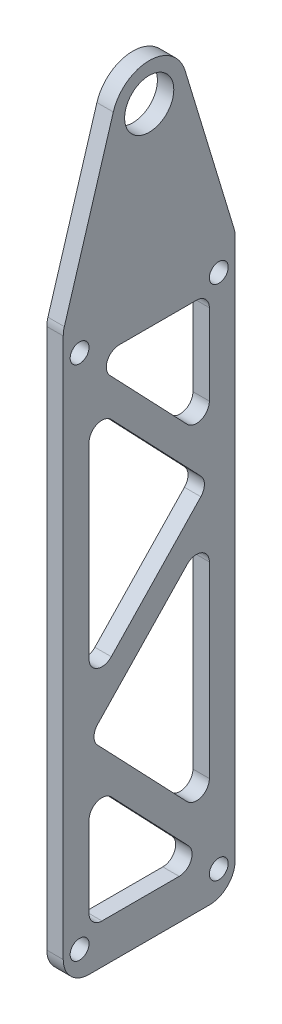
SolidWorks part; units mm, degrees
material "6061 Alloy"
ref_plane "Front Plane" through (0, 0, 0) normal (0, 0, 1) x (1, 0, 0)
ref_plane "Top Plane" through (0, 0, 0) normal (0, 1, 0) x (1, 0, 0)
ref_plane "Right Plane" through (0, 0, 0) normal (1, 0, 0) x (0, 0, -1)
sketch "Sketch1" plane through (0, 0, 0) normal (1, 0, 0) x (0, 0, -1)
  line L0 (-13.4747, 0) -> (13.4747, 0) construction
  line L1 (0, 0) -> (0, 35) construction
  line L2 (-13.4747, 0) -> (0, 35) construction
  line L3 (0, 35) -> (13.4747, 0) construction
  line L4 (13.4747, 0) -> (-13.4747, 0) construction
  line L8 (-13.4747, 0) -> (13.4747, 0) construction
  line L9 (-13.4747, 0) -> (-13.4747, -100) construction
  line L10 (13.4747, 0) -> (13.4747, -100) construction
  line L11 (-13.4747, -100) -> (13.4747, -100) construction
  line L16 (-16.645, -105.15) -> (16.645, -105.15)
  line L17 (-16.645, -105.15) -> (-16.645, 5.15)
  line L18 (16.645, -105.15) -> (16.645, 5.15)
  line L19 (-16.645, 5.15) -> (16.645, 5.15)
  line L20 (-16.645, 5.15) -> (-6.9497, 37.1084)
  line L21 (-6.9497, 37.1084) -> (6.9497, 37.1084) construction
  line L22 (6.9497, 37.1084) -> (16.645, 5.15)
  circle A0 centre (-13.4747, 0) radius 1.8288
  circle A1 centre (0, 35) radius 4.7625
  circle A2 centre (13.4747, 0) radius 1.8288
  circle A3 centre (-13.4747, -100) radius 1.8288
  circle A4 centre (13.4747, -100) radius 1.8288
  arc A5 (-6.9497, 37.1084) -> (6.9497, 37.1084) centre (0, 35) cw
  point P4 (0, 0)
  point P7 (0, -105.15)
  dimension "D3" = 3.6576
  dimension "D4" = 9.525
  dimension "D9" = 2.5
  dimension "D1" = 26.9494
  dimension "D5" = 100
  dimension "D6" = 5.15
  dimension "D7" = 35
  dimension "D8" = 5.15
  dimension "D2" = 33.29
extrude "Boss-Extrude1" add sketch "Sketch1" along normal blind 3.175
sketch "Sketch2" plane through (3.175, 0, 0) normal (1, 0, 0) x (0, 0, -1)
  line L3 (-11.645, -97.42) -> (-11.645, -2.5) construction
  line L4 (11.645, -97.42) -> (11.645, -2.5) construction
  line L5 (-11.645, -2.5) -> (11.645, -2.5) construction
  line L6 (-11.645, -97.42) -> (11.645, -97.42) construction
  line L8 (-16.645, -105.15) -> (-16.645, 5.15) construction
  line L9 (11.645, -2.5) -> (-11.645, -2.5)
  line L10 (-11.645, -2.5) -> (11.645, -26.8987)
  line L11 (11.645, -26.8987) -> (11.645, -2.5)
  line L12 (-11.645, -9.7413) -> (11.645, -34.14)
  line L13 (11.645, -34.14) -> (-11.645, -58.5387)
  line L14 (-11.645, -58.5387) -> (-11.645, -34.14)
  line L15 (11.645, -37.7607) -> (-11.645, -62.1593) construction
  line L16 (-11.645, -34.14) -> (-11.645, -9.7413)
  line L17 (-11.645, -73.0213) -> (-11.645, -97.42)
  line L18 (-11.645, -97.42) -> (11.645, -97.42)
  line L19 (11.645, -97.42) -> (-11.645, -73.0213)
  line L20 (11.645, -41.3813) -> (11.645, -65.78)
  line L21 (11.645, -65.78) -> (11.645, -90.1787)
  line L22 (11.645, -90.1787) -> (-11.645, -65.78)
  line L23 (-11.645, -65.78) -> (11.645, -41.3813)
  line L24 (16.645, -105.15) -> (16.645, 5.15) construction
  circle A1 centre (13.4747, 0) radius 1.8288 construction
  circle A3 centre (13.4747, -100) radius 1.8288 construction
  point P0 (11.645, -49.96)
  point P2 (0, -97.42)
  point P28 (0, -49.96)
  dimension "D4" = 2.58
  dimension "D1" = 5
  dimension "D2" = 5
  dimension "D3" = 2.5
  dimension "D5" = 5
  dimension "D6" = 2.5
  dimension "D7" = 2
extrude "Cut-Extrude1" cut sketch "Sketch2" against normal through all
fillet "Fillet1" radius 2.5 12 edges at (1.5875, -97.42, -11.645) (1.5875, -90.1787, -11.645) (1.5875, -41.3813, -11.645) (1.5875, -73.0213, 11.645) (1.5875, -97.42, 11.645) (1.5875, -65.78, 11.645) (1.5875, -58.5387, 11.645) (1.5875, -34.14, -11.645) (1.5875, -9.7413, 11.645) (1.5875, -2.5, 11.645) (1.5875, -26.8987, -11.645) (1.5875, -2.5, -11.645)
fillet "Fillet2" radius 5 4 edges at (1.5875, 5.15, 16.645) (1.5875, 5.15, -16.645) (1.5875, -105.15, -16.645) (1.5875, -105.15, 16.645)
